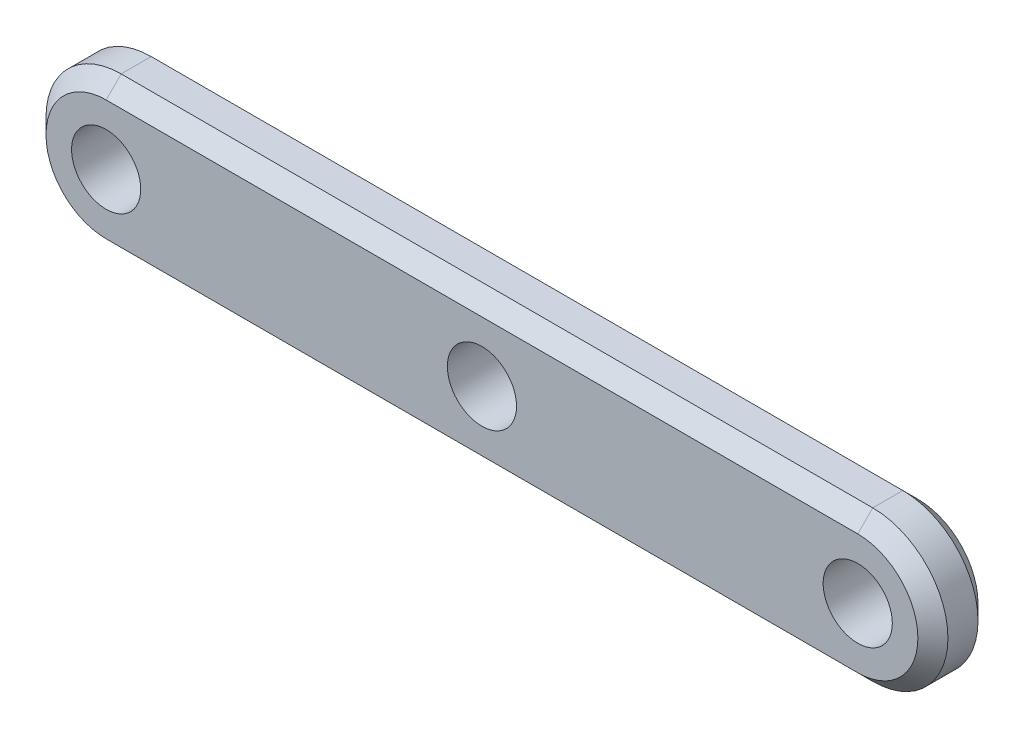
SolidWorks part; units mm, degrees
material "Copper"
ref_plane "Front Plane" through (0, 0, 0) normal (0, 0, 1) x (1, 0, 0)
ref_plane "Top Plane" through (0, 0, 0) normal (0, 1, 0) x (1, 0, 0)
ref_plane "Right Plane" through (0, 0, 0) normal (1, 0, 0) x (0, 0, -1)
sketch "Sketch1" plane through (0, 0, 0) normal (0, 0, 1) x (1, 0, 0)
  line L0 (0, 5) -> (50, 5)
  line L1 (50, -5) -> (0, -5)
  line L2 (0, 0) -> (50, 0) construction
  circle A0 centre (0, 0) radius 5
  circle A1 centre (50, 0) radius 5
  circle A2 centre (50, 0) radius 2.3
  circle A3 centre (0, 0) radius 2.3
  circle A4 centre (25, 0) radius 2.3
  dimension "D1" = 10
  dimension "D2" = 50
  dimension "D3" = 4.6
extrude "Boss-Extrude1" add sketch "Sketch1" along normal blind 4 contours A1 L0 A0 L1 | A1 A2 | A0 A3 | L2 A0 L1 A1 A4
chamfer "Chamfer1" distance 1 angle 45 8 edges at (25, -5, 0) (-5, 0, 0) (55, 0, 0) (25, 5, 0) (25, -5, 4) (-5, 0, 4) (55, 0, 4) (25, 5, 4)
